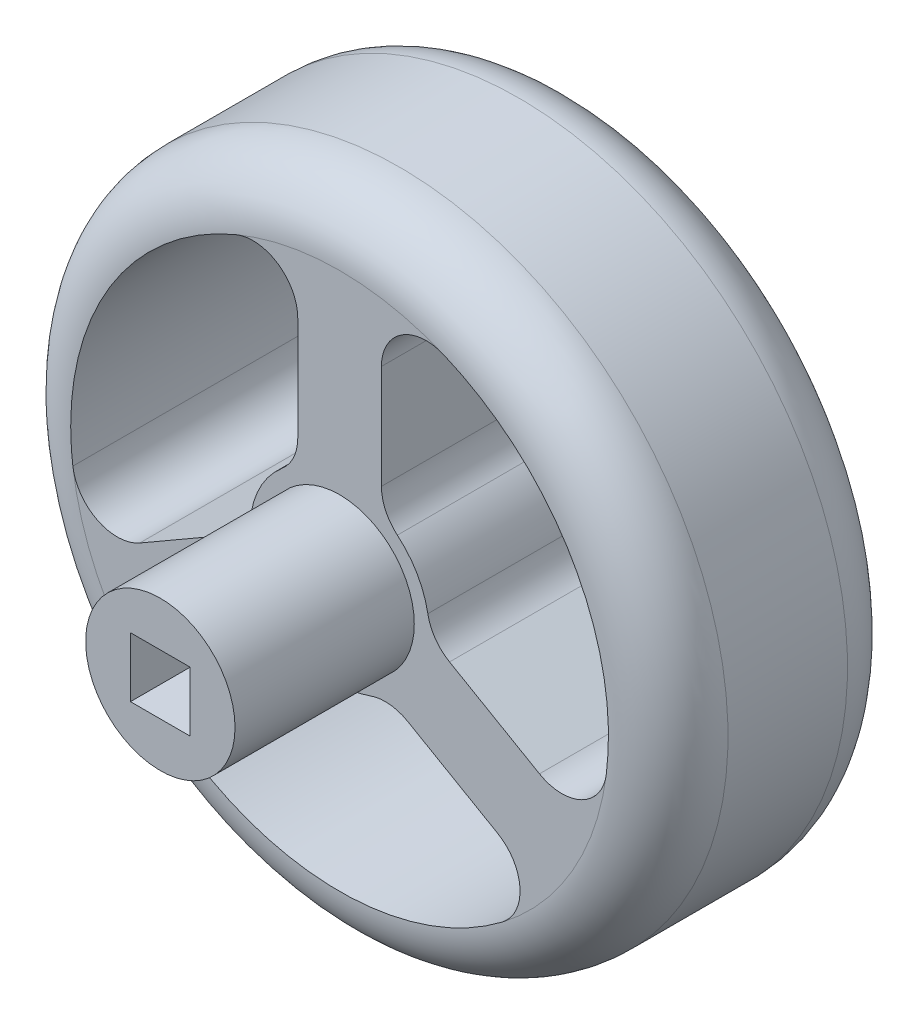
SolidWorks part; units mm, degrees
material "Rubber"
ref_plane "Front Plane" through (0, 0, 0) normal (0, 0, 1) x (1, 0, 0)
ref_plane "Top Plane" through (0, 0, 0) normal (0, 1, 0) x (1, 0, 0)
ref_plane "Right Plane" through (0, 0, 0) normal (1, 0, 0) x (0, 0, -1)
sketch "Sketch1" plane through (0, 0, 0) normal (0, 0, 1) x (1, 0, 0)
  circle A0 centre (0, 0) radius 27.94
  dimension "D1" = 55.88
extrude "Boss-Extrude1" add sketch "Sketch1" along normal blind 20.32
sketch "Sketch2" plane through (0, 0, 0) normal (0, 0, -1) x (-1, 0, 0)
  circle A0 centre (0, 0) radius 6.35
  dimension "D2" = 12.7
extrude "Boss-Extrude2" add sketch "Sketch2" along normal blind 20.32
sketch "Sketch3" plane through (0, 0, -20.32) normal (0, 0, -1) x (-1, 0, 0)
  circle A0 centre (0, 0) radius 27.94
  dimension "D2" = 55.88
extrude "Boss-Extrude3" add sketch "Sketch3" along normal blind 20.32
fillet "Fillet1" radius 5.08 1 edges at (27.94, 0, 20.32)
fillet "Fillet2" radius 5.08 1 edges at (27.94, 0, 0)
fillet "Fillet3" radius 5.08 1 edges at (-27.94, 0, -20.32)
fillet "Fillet4" radius 5.08 1 edges at (-27.94, 0, -40.64)
sketch "Sketch4" plane through (0, 0, -40.64) normal (0, 0, -1) x (-1, 0, 0)
  line L0 (0, 7.62) -> (0, 22.86) construction
  line L1 (-3.556, 8.74) -> (-3.556, 17.5683)
  line L2 (3.556, 8.74) -> (3.556, 17.5683)
  line L3 (9.347, -1.2904) -> (16.9926, -5.7046)
  line L4 (5.791, -7.4496) -> (13.4366, -11.8637)
  line L5 (-5.791, -7.4496) -> (-13.4366, -11.8637)
  line L6 (-9.347, -1.2904) -> (-16.9926, -5.7046)
  arc A0 (-13.8379, -18.1959) -> (13.8379, -18.1959) centre (0, 0) ccw
  arc A1 (7.5014, 1.3394) -> (4.9107, 5.8266) centre (0, 0) ccw
  arc A2 (-4.9107, 5.8266) -> (-7.5014, 1.3394) centre (0, 0) ccw
  arc A3 (-2.5907, -7.1661) -> (2.5907, -7.1661) centre (0, 0) ccw
  arc A4 (-3.556, 17.5683) -> (-8.8392, 21.0819) centre (-7.366, 17.5683) ccw
  arc A5 (8.8392, 21.0819) -> (3.556, 17.5683) centre (7.366, 17.5683) ccw
  arc A6 (-4.9107, 5.8266) -> (-3.556, 8.74) centre (-7.366, 8.74) ccw
  arc A7 (3.556, 8.74) -> (4.9107, 5.8266) centre (7.366, 8.74) ccw
  arc A8 (16.9926, -5.7046) -> (22.6771, -2.886) centre (18.8976, -2.405) ccw
  arc A9 (7.5014, 1.3394) -> (9.347, -1.2904) centre (11.252, 2.0092) ccw
  arc A10 (5.791, -7.4496) -> (2.5907, -7.1661) centre (3.886, -10.7491) ccw
  arc A11 (13.8379, -18.1959) -> (13.4366, -11.8637) centre (11.5316, -15.1633) ccw
  arc A12 (-13.4366, -11.8637) -> (-13.8379, -18.1959) centre (-11.5316, -15.1633) ccw
  arc A13 (-2.5907, -7.1661) -> (-5.791, -7.4496) centre (-3.886, -10.7491) ccw
  arc A14 (-9.347, -1.2904) -> (-7.5014, 1.3394) centre (-11.252, 2.0092) ccw
  arc A15 (-22.6771, -2.886) -> (-16.9926, -5.7046) centre (-18.8976, -2.405) ccw
  arc A16 (22.6771, -2.886) -> (8.8392, 21.0819) centre (0, 0) ccw
  arc A17 (-8.8392, 21.0819) -> (-22.6771, -2.886) centre (0, 0) ccw
  point P46 (0, 0)
  dimension "D2" = 45.72
  dimension "D3" = 15.24
  dimension "D6" = 7.62
  dimension "D7" = 7.62
  dimension "D8" = 7.62
  dimension "D9" = 7.62
  dimension "D4" = 3.556
  dimension "D5" = 3.556
  dimension "D10" = 3
sketch "Sketch5" plane through (0, 0, 0) normal (0, 1, 0) x (1, 0, 0)
  line L0 (0, 32.8922) -> (0, -10.16) construction
extrude "Cut-Extrude1" cut sketch "Sketch4" against normal through all
ref_plane "Plane1" through (0, 0, 0) normal (0, 0, -1) x (-1, 0, 0)
sketch "Sketch6" plane through (0, 0, 0) normal (0, 0, -1) x (-1, 0, 0)
  circle A0 centre (0, 0) radius 27.94
extrude "Cut-Extrude2" cut sketch "Sketch6" against normal through all
sketch "Sketch7" plane through (0, 0, 0) normal (0, 0, 1) x (1, 0, 0)
  circle A1 centre (0, 0) radius 6.35
  circle A2 centre (0, 0) radius 6.35
  dimension "D1" = 0
extrude "Cut-Extrude3" cut sketch "Sketch7" against normal blind 5.08
sketch "Sketch8" plane through (0, 0, -5.08) normal (0, 0, 1) x (1, 0, 0)
  line L1 (-2.54, 2.54) -> (2.54, 2.54)
  line L2 (-2.54, 2.54) -> (-2.54, -2.54)
  line L3 (-2.54, -2.54) -> (2.54, -2.54)
  line L4 (2.54, 2.54) -> (2.54, -2.54)
  line L5 (-2.54, 2.54) -> (2.54, -2.54) construction
  line L6 (-2.54, -2.54) -> (2.54, 2.54) construction
  circle A1 centre (0, 0) radius 6.35
  circle A2 centre (0, 0) radius 6.35 construction
  dimension "D2" = 5.08
  dimension "D3" = 5.08
  dimension "D1" = 0
extrude "Cut-Extrude4" cut sketch "Sketch8" against normal blind 12.7
